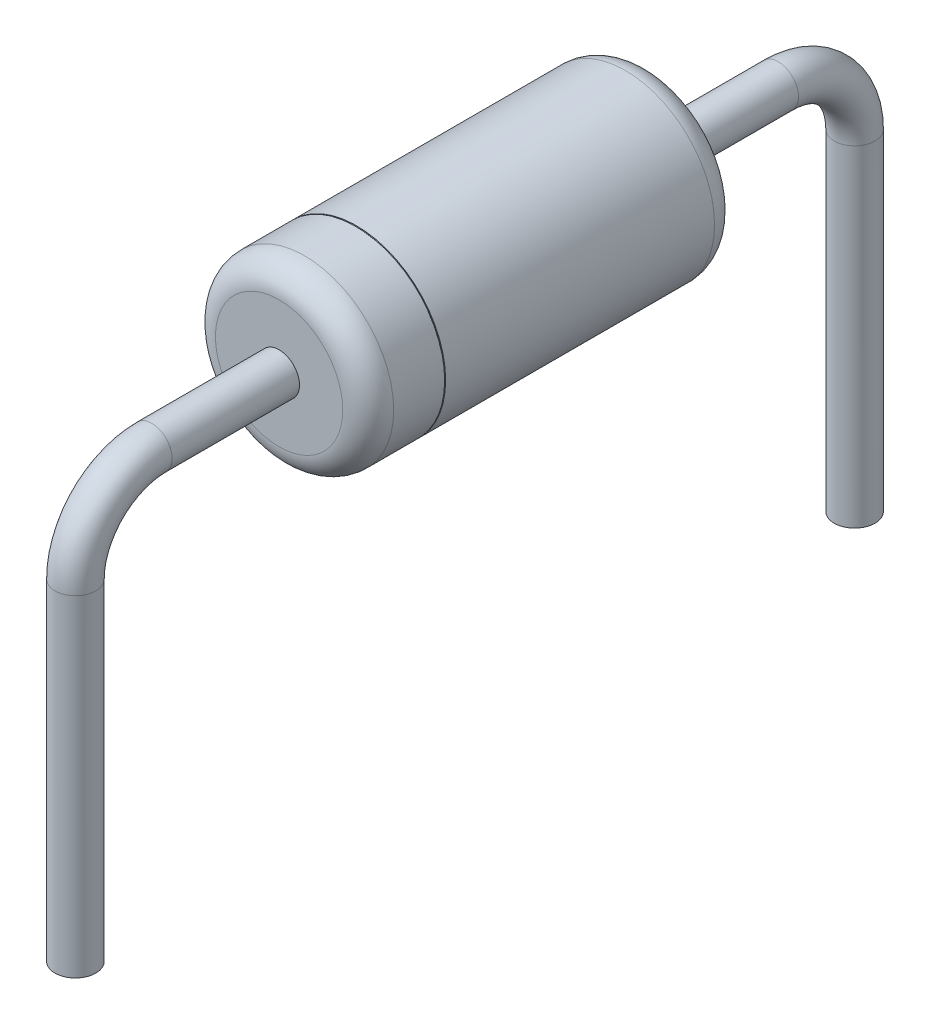
SolidWorks part; units mm, degrees
ref_plane "Front Plane" through (0, 0, 0) normal (0, 0, 1) x (1, 0, 0)
ref_plane "Top Plane" through (0, 0, 0) normal (0, 1, 0) x (1, 0, 0)
ref_plane "Right Plane" through (0, 0, 0) normal (1, 0, 0) x (0, 0, -1)
sketch "Sketch1" plane through (0, 0, 0) normal (1, 0, 0) x (0, 0, -1)
  line L0 (-2.8942, 0) -> (-1.33, 0) construction
  line L1 (-1.83, 0.875) -> (-1.33, 0.875)
  line L2 (-2.08, 0.625) -> (-2.08, 0)
  line L3 (-2.08, 0) -> (-2.08, -0.8858) construction
  line L4 (1.57, 0.625) -> (1.57, 0)
  line L5 (-1.33, 0.875) -> (-1.33, 0.865)
  line L6 (-1.32, 0.875) -> (-1.32, 0.865)
  line L7 (-1.32, 0) -> (-1.33, 0) construction
  line L8 (-1.33, 0.875) -> (-1.32, 0.875) construction
  line L9 (-1.32, 0.875) -> (1.32, 0.875)
  line L10 (-1.33, 0.865) -> (-1.32, 0.865)
  line L11 (-1.33, 0.865) -> (-1.33, 0) construction
  line L12 (-1.32, 0.865) -> (-1.32, 0) construction
  line L13 (-1.33, 0) -> (-1.32, 0) construction
  line L14 (-1.32, 0) -> (2.8159, 0) construction
  line L15 (-2.08, 0) -> (1.57, 0)
  arc A0 (1.57, 0.625) -> (1.32, 0.875) centre (1.32, 0.625) ccw
  arc A1 (-2.08, 0.625) -> (-1.83, 0.875) centre (-1.83, 0.625) cw
  point P5 (0, 0.875)
  point P17 (1.57, 0.875)
  point P20 (-2.08, 0.875)
  dimension "D6" = 0.25
  dimension "D1" = 3.65
  dimension "D2" = 1.75
  dimension "D3" = 0.75
  dimension "D4" = 0.01
  dimension "D5" = 0.01
revolve "Revolve1" add sketch "Sketch1" angle 360 about L15
sketch "Sketch2" plane through (0, 0, 0) normal (1, 0, 0) x (0, 0, -1)
  line L0 (0, 0) -> (-3.33, 0)
  line L1 (-2.08, 0.625) -> (-2.08, -0.625) construction
  line L2 (0, 0) -> (2.82, 0)
  line L3 (1.57, -0.625) -> (1.57, 0.625) construction
  line L4 (-4.08, -0.75) -> (-4.08, -4)
  line L5 (3.57, -0.75) -> (3.57, -4)
  arc A0 (-4.08, -0.75) -> (-3.33, 0) centre (-3.33, -0.75) cw
  arc A1 (3.57, -0.75) -> (2.82, 0) centre (2.82, -0.75) ccw
  point P12 (-4.08, 0)
  point P15 (3.57, 0)
  dimension "D3" = 0.75
  dimension "D1" = 2
  dimension "D2" = 2
  dimension "D4" = 4
sweep "Sweep1" add path "Sketch2" circular profile diameter 0.4 parameters "D3"=0.4
